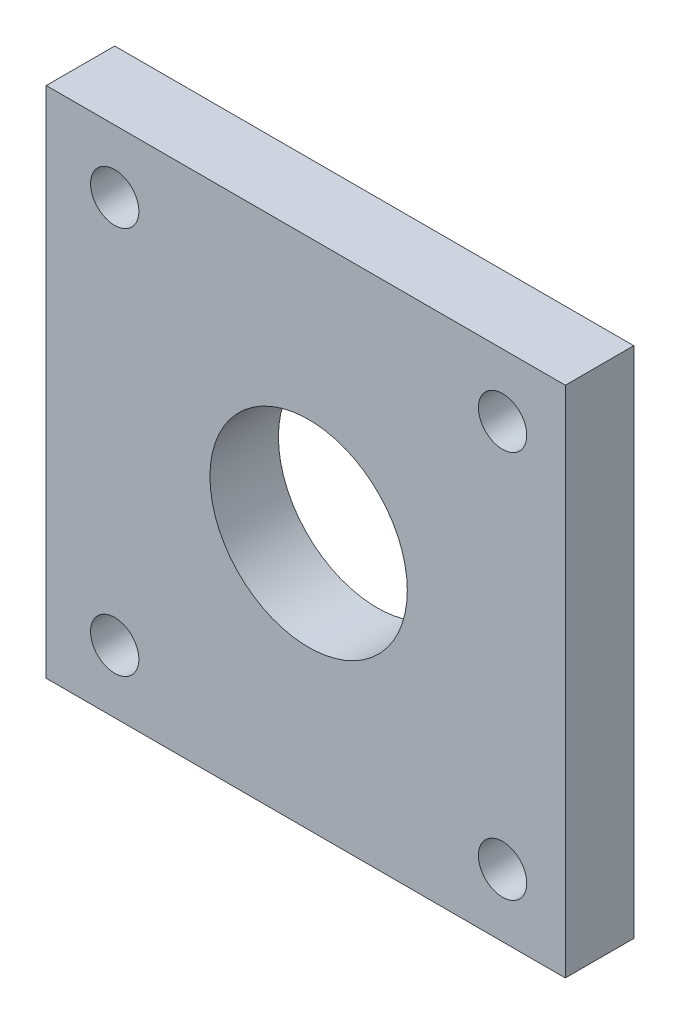
SolidWorks part; units mm, degrees
ref_plane "Front Plane" through (0, 0, 0) normal (0, 0, 1) x (1, 0, 0)
ref_plane "Top Plane" through (0, 0, 0) normal (0, 1, 0) x (1, 0, 0)
ref_plane "Right Plane" through (0, 0, 0) normal (1, 0, 0) x (0, 0, -1)
sketch "Sketch1" plane through (0, 0, 0) normal (0, 0, 1) x (1, 0, 0)
  line L0 (-23, -22.5) -> (22.5, -22.5)
  line L1 (22.5, -22.5) -> (22.5, 22.5)
  line L2 (22.5, 22.5) -> (-23, 22.5)
  line L3 (-23, 22.5) -> (-23, -22.5)
  circle A0 centre (0, 0) radius 8.65
  circle A1 centre (-17, -17) radius 2.12
  circle A2 centre (-17, 17) radius 2.12
  circle A3 centre (17, -17) radius 2.12
  circle A4 centre (17, 17) radius 2.12
extrude "Six mm head plate bolts to 34 mm square pattern" add sketch "Sketch1" along normal blind 6
sketch "Sketch2" plane through (0, 0, 0) normal (1, 0, 0) x (0, 0, -1)
  circle A0 centre (-3, -9) radius 2.12
  circle A1 centre (-3, 9) radius 2.12
extrude "Mounting toe tapped from bottom" cut sketch "Sketch2" along normal blind 7 from offset 23
